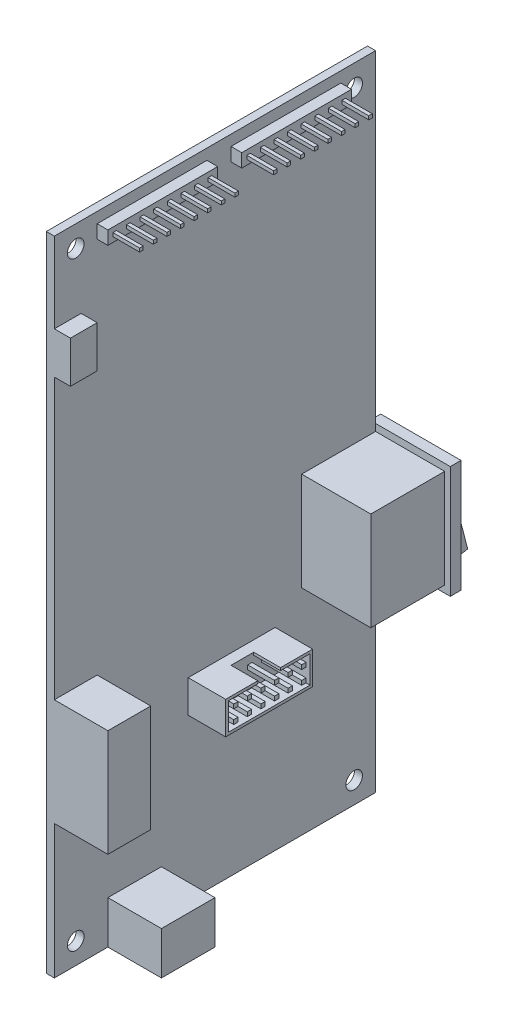
SolidWorks part; units mm, degrees
ref_plane "Płaszczyzna przednia" through (0, 0, 0) normal (0, 0, 1) x (1, 0, 0)
ref_plane "Płaszczyzna górna" through (0, 0, 0) normal (0, 1, 0) x (1, 0, 0)
ref_plane "Płaszczyzna prawa" through (0, 0, 0) normal (1, 0, 0) x (0, 0, -1)
sketch "Szkic3" plane through (407.1513, 0, 0) normal (-1, 0, 0) x (0, 0, 1)
  line L0 (842.3593, 214.2409) -> (842.3593, 94.2409)
  line L1 (842.3593, 214.2409) -> (902.3593, 214.2409)
  line L2 (842.3593, 94.2409) -> (902.3593, 94.2409)
  line L3 (902.3593, 214.2409) -> (902.3593, 94.2409)
  dimension "D1" = 60
  dimension "D2" = 120
extrude "Dodanie-wyciągnięcie1" add sketch "Szkic3" along normal blind 1.5
sketch "Szkic4" plane through (407.1513, 0, 0) normal (1, 0, 0) x (0, 0, -1)
  line L0 (-894.3593, 212.2409) -> (-873.8593, 212.2409)
  line L1 (-873.8593, 212.2409) -> (-873.8593, 209.7409)
  line L2 (-873.8593, 209.7409) -> (-894.3593, 209.7409)
  line L3 (-894.3593, 209.7409) -> (-894.3593, 212.2409)
  line L4 (-902.3593, 94.2409) -> (-902.3593, 214.2409) construction
  line L5 (-902.3593, 214.2409) -> (-842.3593, 214.2409) construction
  dimension "D1" = 20.5
  dimension "D2" = 2.5
  dimension "D3" = 8
  dimension "D4" = 2
extrude "Dodanie-wyciągnięcie2" add sketch "Szkic4" along normal blind 2
sketch "Szkic5" plane through (409.1513, 0, 0) normal (1, 0, 0) x (0, 0, -1)
  line L0 (-893.4193, 211.3409) -> (-893.4193, 210.6809)
  line L1 (-893.4193, 211.3409) -> (-892.7593, 211.3409)
  line L2 (-893.4193, 210.6809) -> (-892.7593, 210.6809)
  line L3 (-892.7593, 211.3409) -> (-892.7593, 210.6809)
  line L4 (-894.3593, 212.2409) -> (-894.3593, 209.7409) construction
  line L5 (-894.3593, 209.7409) -> (-873.8593, 209.7409) construction
  point P0 (-894.3593, 210.9909)
  dimension "D1" = 0.66
  dimension "D2" = 0.66
  dimension "D3" = 0.94
  dimension "D4" = 0.94
extrude "Dodanie-wyciągnięcie3" add sketch "Szkic5" along normal blind 5
pattern_linear "Szyk liniowy1" count 8 spacing 2.54 along (0, 0, -1) of "Dodanie-wyciągnięcie3"
sketch "Szkic6" plane through (407.1513, 0, 0) normal (1, 0, 0) x (0, 0, -1)
  line L0 (-877.3593, 130.3209) -> (-861.1193, 130.3209)
  line L1 (-861.1193, 130.3209) -> (-861.1193, 124.2409)
  line L2 (-861.1193, 124.2409) -> (-877.3593, 124.2409)
  line L3 (-877.3593, 124.2409) -> (-877.3593, 130.3209)
  line L4 (-842.3593, 94.2409) -> (-902.3593, 94.2409) construction
  line L5 (-902.3593, 94.2409) -> (-902.3593, 214.2409) construction
  dimension "D1" = 30
  dimension "D2" = 25
  dimension "D3" = 16.24
extrude "Dodanie-wyciągnięcie4" add sketch "Szkic6" along normal blind 2
sketch "Szkic7" plane through (409.1513, 0, 0) normal (1, 0, 0) x (0, 0, -1)
  line L6 (-875.8593, 128.8209) -> (-875.8593, 128.0209)
  line L7 (-875.8593, 128.8209) -> (-875.0593, 128.8209)
  line L8 (-875.8593, 128.0209) -> (-875.0593, 128.0209)
  line L9 (-875.0593, 128.8209) -> (-875.0593, 128.0209)
  line L10 (-861.1193, 130.3209) -> (-877.3593, 130.3209) construction
  line L11 (-877.3593, 130.3209) -> (-877.3593, 124.2409) construction
  dimension "D1" = 0.8
  dimension "D2" = 0.8
  dimension "D3" = 1.5
  dimension "D4" = 1.5
extrude "Dodanie-wyciągnięcie5" add sketch "Szkic7" along normal blind 5
pattern_linear "Szyk liniowy2" count 6 spacing 2.54 along (0, 0, -1) count 2 spacing 2.54 along (0, -1, 0) of "Dodanie-wyciągnięcie5"
sketch "Szkic8" plane through (409.1513, 0, 0) normal (1, 0, 0) x (0, 0, -1)
  line L0 (-876.8593, 129.8209) -> (-876.8593, 124.7409)
  line L1 (-876.8593, 124.7409) -> (-861.6193, 124.7409)
  line L2 (-861.6193, 124.7409) -> (-861.6193, 129.8209)
  line L3 (-861.6193, 129.8209) -> (-867.1193, 129.8209)
  line L4 (-877.3593, 130.3209) -> (-877.3593, 124.2409)
  line L5 (-877.3593, 130.3209) -> (-877.3593, 124.2409)
  line L6 (-877.3593, 124.2409) -> (-861.1193, 124.2409)
  line L7 (-877.3593, 124.2409) -> (-861.1193, 124.2409)
  line L8 (-861.1193, 124.2409) -> (-861.1193, 130.3209)
  line L9 (-861.1193, 124.2409) -> (-861.1193, 130.3209)
  line L10 (-861.1193, 130.3209) -> (-877.3593, 130.3209)
  line L11 (-861.1193, 130.3209) -> (-867.1193, 130.3209)
  line L12 (-871.3593, 130.3209) -> (-871.3593, 129.8209)
  line L13 (-867.1193, 130.3209) -> (-867.1193, 129.8209)
  line L14 (-871.3593, 130.3209) -> (-877.3593, 130.3209)
  line L15 (-871.3593, 129.8209) -> (-876.8593, 129.8209)
  line L16 (-861.1193, 130.3209) -> (-877.3593, 130.3209) construction
  line L18 (-861.6193, 129.8209) -> (-876.8593, 129.8209) construction
  point P0 (-930.3593, 74.2409)
  point P2 (-929.8593, 89.9809)
  point P4 (-930.3593, 90.4809)
  point P5 (-929.8593, 74.7409)
  dimension "D3" = 6
  dimension "D4" = 6
  dimension "D1" = 0
  dimension "D2" = 0.5
extrude "Dodanie-wyciągnięcie6" add sketch "Szkic8" along normal blind 5
sketch "Szkic9" plane through (407.1513, 0, 0) normal (1, 0, 0) x (0, 0, -1)
  line L0 (-892.3593, 94.2409) -> (-892.3593, 102.2409)
  line L1 (-842.3593, 94.2409) -> (-902.3593, 94.2409) construction
  line L2 (-892.3593, 102.2409) -> (-882.3593, 102.2409)
  line L3 (-882.3593, 102.2409) -> (-882.3593, 94.2409)
  line L4 (-882.3593, 94.2409) -> (-892.3593, 94.2409)
  line L5 (-842.3593, 214.2409) -> (-842.3593, 94.2409) construction
  dimension "D1" = 10
  dimension "D2" = 8
  dimension "D3" = 40
extrude "Dodanie-wyciągnięcie7" add sketch "Szkic9" along normal blind 10
sketch "Szkic10" plane through (407.1513, 0, 0) normal (1, 0, 0) x (0, 0, -1)
  line L1 (-892.3593, 94.2409) -> (-902.3593, 94.2409) construction
  line L5 (-902.3593, 94.2409) -> (-902.3593, 214.2409) construction
  line L6 (-902.3593, 119.2409) -> (-902.3593, 139.2409)
  line L7 (-902.3593, 119.2409) -> (-894.3593, 119.2409)
  line L8 (-902.3593, 139.2409) -> (-894.3593, 139.2409)
  line L9 (-894.3593, 119.2409) -> (-894.3593, 139.2409)
  dimension "D4" = 20
  dimension "D5" = 8
  dimension "D6" = 25
extrude "Dodanie-wyciągnięcie8" add sketch "Szkic10" along normal blind 10
sketch "Szkic11" plane through (407.1513, 0, 0) normal (1, 0, 0) x (0, 0, -1)
  line L0 (-902.3593, 214.2409) -> (-842.3593, 214.2409) construction
  line L1 (-902.3593, 94.2409) -> (-902.3593, 119.2409) construction
  circle A0 centre (-898.3593, 210.2409) radius 1.55
  dimension "D1" = 4
  dimension "D2" = 3.1
  dimension "D3" = 4
extrude "Wytnij-wyciągnięcie2" cut sketch "Szkic11" against normal blind 10
pattern_linear "Szyk liniowy3" count 2 spacing 52 along (0, 0, -1) count 2 spacing 112 along (0, -1, 0) of "Wytnij-wyciągnięcie2"
sketch "Szkic12" plane through (407.1513, 0, 0) normal (1, 0, 0) x (0, 0, -1)
  line L1 (-902.3593, 214.2409) -> (-842.3593, 214.2409) construction
  line L6 (-902.3593, 199.2409) -> (-902.3593, 191.4409)
  line L7 (-902.3593, 199.2409) -> (-897.3593, 199.2409)
  line L8 (-902.3593, 191.4409) -> (-897.3593, 191.4409)
  line L9 (-897.3593, 199.2409) -> (-897.3593, 191.4409)
  line L10 (-902.3593, 139.2409) -> (-902.3593, 214.2409) construction
  dimension "D4" = 5
  dimension "D5" = 7.8
  dimension "D6" = 15
extrude "Dodanie-wyciągnięcie9" add sketch "Szkic12" along normal blind 3
sketch "Szkic13" plane through (407.1513, 0, 0) normal (1, 0, 0) x (0, 0, -1)
  line L0 (-856.1593, 152.6409) -> (-856.1593, 134.2409)
  line L1 (-856.1593, 152.6409) -> (-842.3593, 152.6409)
  line L2 (-856.1593, 134.2409) -> (-842.3593, 134.2409)
  line L3 (-842.3593, 134.2409) -> (-842.3593, 132.9409)
  line L4 (-842.3593, 153.9409) -> (-842.3593, 152.6409)
  line L5 (-842.3593, 153.9409) -> (-840.3593, 153.9409)
  line L6 (-842.3593, 132.9409) -> (-840.3593, 132.9409)
  line L7 (-840.3593, 153.9409) -> (-840.3593, 132.9409)
  line L8 (-842.3593, 214.2409) -> (-842.3593, 94.2409) construction
  line L10 (-842.3593, 94.2409) -> (-882.3593, 94.2409) construction
  point P20 (-842.0121, 122.3788)
  point P23 (-835.7765, 105.9703)
  dimension "D1" = 13.8
  dimension "D2" = 40
  dimension "D3" = 2
  dimension "D4" = 18.4
  dimension "D5" = 2
  dimension "D6" = 1.3
  dimension "D7" = 21
  dimension "D8" = 13.8
extrude "Dodanie-wyciągnięcie11" add sketch "Szkic13" along normal blind 12.9 separate body
pattern_linear "Szyk liniowy7" count 2 spacing 25 along (0, 0, -1) of "Dodanie-wyciągnięcie2", "Dodanie-wyciągnięcie3", "Szyk liniowy1"
sketch "Szkic14" plane through (420.0513, 0, 0) normal (1, 0, 0) x (0, 0, -1)
  line L0 (-842.3593, 132.9409) -> (-840.3593, 132.9409)
  line L1 (-842.3593, 132.9409) -> (-842.3593, 153.9409)
  line L2 (-840.3593, 132.9409) -> (-840.3593, 153.9409)
  line L3 (-842.3593, 153.9409) -> (-840.3593, 153.9409)
  line L4 (-840.3593, 153.9409) -> (-842.3593, 153.9409) construction
  point P0 (-841.3593, 153.9409)
  dimension "D1" = 0
extrude "Dodanie-wyciągnięcie12" add sketch "Szkic14" along normal blind 1.05
sketch "Szkic15" plane through (407.1513, 0, 0) normal (-1, 0, 0) x (0, 0, 1)
  line L0 (842.3593, 132.9409) -> (840.3593, 132.9409)
  line L1 (842.3593, 132.9409) -> (842.3593, 153.9409)
  line L2 (840.3593, 132.9409) -> (840.3593, 153.9409)
  line L3 (842.3593, 153.9409) -> (840.3593, 153.9409)
  line L4 (840.3593, 153.9409) -> (842.3593, 153.9409) construction
  dimension "D1" = 0
extrude "Dodanie-wyciągnięcie13" add sketch "Szkic15" along normal blind 1.05
sketch "Szkic16" plane through (420.0513, 0, 0) normal (1, 0, 0) x (0, 0, -1)
  line L0 (-840.3593, 151.1409) -> (-840.3593, 135.7409)
  line L1 (-840.3593, 135.7409) -> (-836.5593, 136.4409)
  line L2 (-840.3593, 151.1409) -> (-836.5593, 136.4409)
  line L3 (-842.3593, 152.6409) -> (-856.1593, 152.6409) construction
  line L4 (-856.1593, 134.2409) -> (-842.3593, 134.2409) construction
  line L5 (-840.3593, 132.9409) -> (-840.3593, 153.9409) construction
  dimension "D1" = 0.7
  dimension "D2" = 1.5
  dimension "D3" = 1.5
  dimension "D4" = 3.8
  dimension "D5" = 0
extrude "Dodanie-wyciągnięcie14" add sketch "Szkic16" against normal blind 11.3 separate body
sketch "Szkic17" plane through (420.0513, 0, 0) normal (1, 0, 0) x (0, 0, -1)
  line L3 (-836.5593, 136.4409) -> (-840.3593, 151.1409)
  line L4 (-840.3593, 151.1409) -> (-840.3593, 135.7409)
  line L5 (-840.3593, 135.7409) -> (-836.5593, 136.4409)
  line L6 (-836.5593, 136.4409) -> (-840.3593, 151.1409)
  line L7 (-840.3593, 151.1409) -> (-840.3593, 135.7409)
  line L8 (-840.3593, 135.7409) -> (-836.5593, 136.4409)
  dimension "D1" = 0
extrude "Wytnij-wyciągnięcie3" cut sketch "Szkic17" against normal blind 1.5
